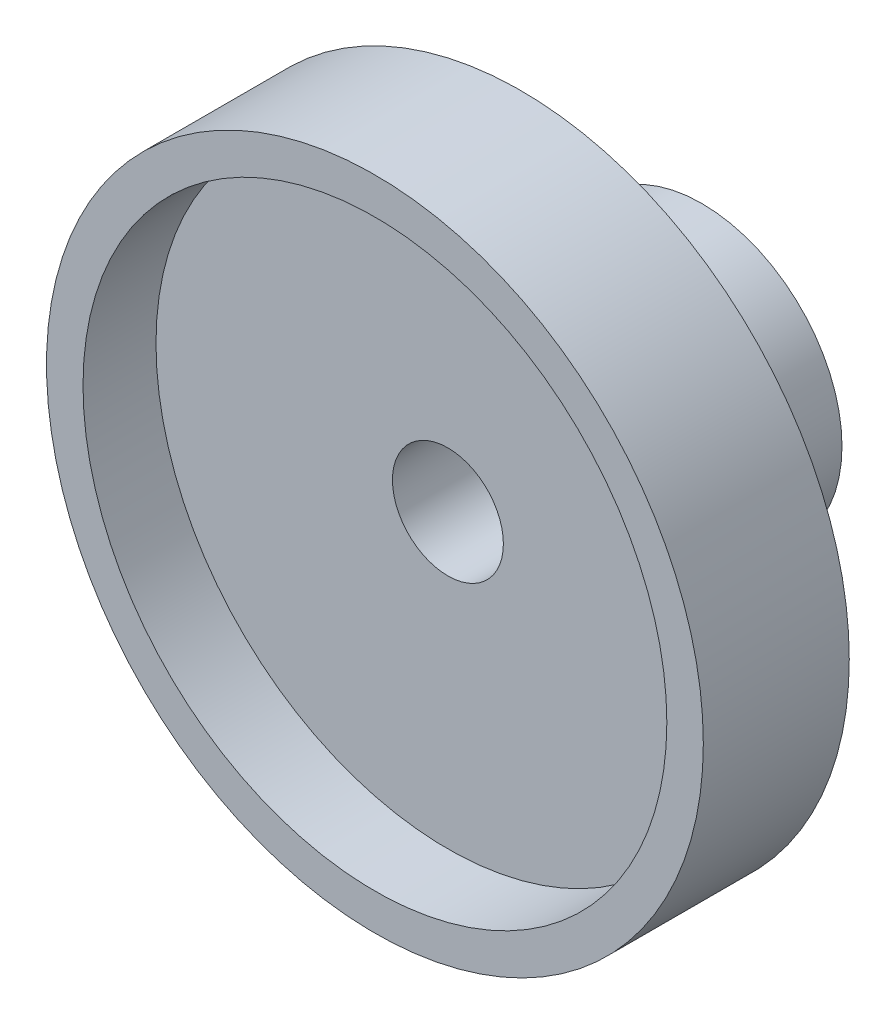
SolidWorks part; units mm, degrees
ref_plane "Front Plane" through (0, 0, 0) normal (0, 0, 1) x (1, 0, 0)
ref_plane "Top Plane" through (0, 0, 0) normal (0, 1, 0) x (1, 0, 0)
ref_plane "Right Plane" through (0, 0, 0) normal (1, 0, 0) x (0, 0, -1)
sketch "Sketch1" plane through (0, 0, 0) normal (0, 0, 1) x (1, 0, 0)
  circle A0 centre (0, 0) radius 14.2875
  dimension "D1" = 28.575
extrude "Boss-Extrude1" add sketch "Sketch1" along normal blind 6.35
sketch "Sketch2" plane through (0, 0, 6.35) normal (0, 0, 1) x (1, 0, 0)
  circle A0 centre (0, 0) radius 12.7
  dimension "D1" = 25.4
extrude "Cut-Extrude1" cut sketch "Sketch2" against normal blind 3.175
sketch "Sketch3" plane through (0, 0, 0) normal (0, 0, -1) x (-1, 0, 0)
  circle A0 centre (0, 0) radius 6.096
  dimension "D1" = 12.192
extrude "Boss-Extrude2" add sketch "Sketch3" along normal blind 7.874
sketch "Sketch4" plane through (0, 0, -7.874) normal (0, 0, -1) x (-1, 0, 0)
  circle A0 centre (0, 0) radius 2.413
  dimension "D1" = 4.826
extrude "Cut-Extrude2" cut sketch "Sketch4" against normal up to surface (11.049 mm away) up to face at (12.7, 0, 3.175)
